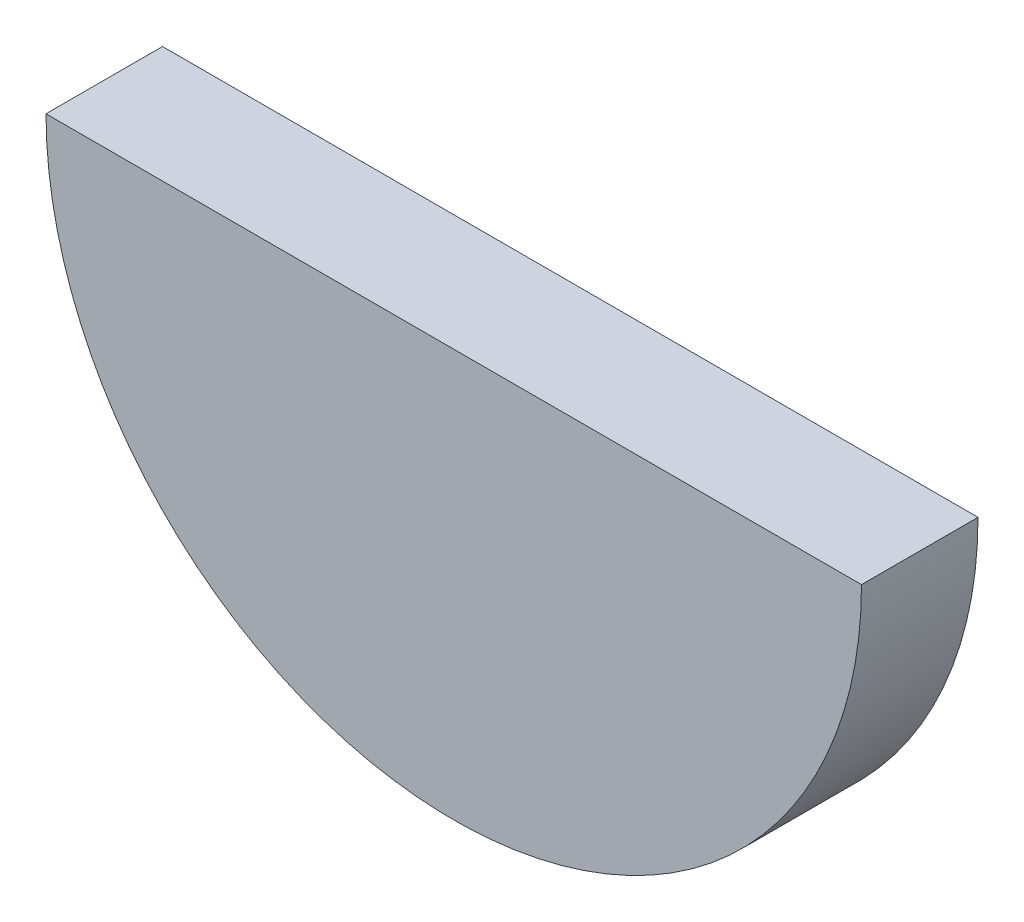
SolidWorks part; units mm, degrees
material "Acrylic (Medium-high impact)"
ref_plane "Front Plane" through (0, 0, 0) normal (0, 0, 1) x (1, 0, 0)
ref_plane "Top Plane" through (0, 0, 0) normal (0, 1, 0) x (1, 0, 0)
ref_plane "Right Plane" through (0, 0, 0) normal (1, 0, 0) x (0, 0, -1)
sketch "Sketch1" plane through (0, 0, 0) normal (0, 0, 1) x (1, 0, 0)
  line L0 (-22.225, 0) -> (22.225, 0)
  arc A0 (-22.225, 0) -> (22.225, 0) centre (0, 0) ccw
  dimension "D1" = 44.45
extrude "Boss-Extrude1" add sketch "Sketch1" along normal blind 6.35
